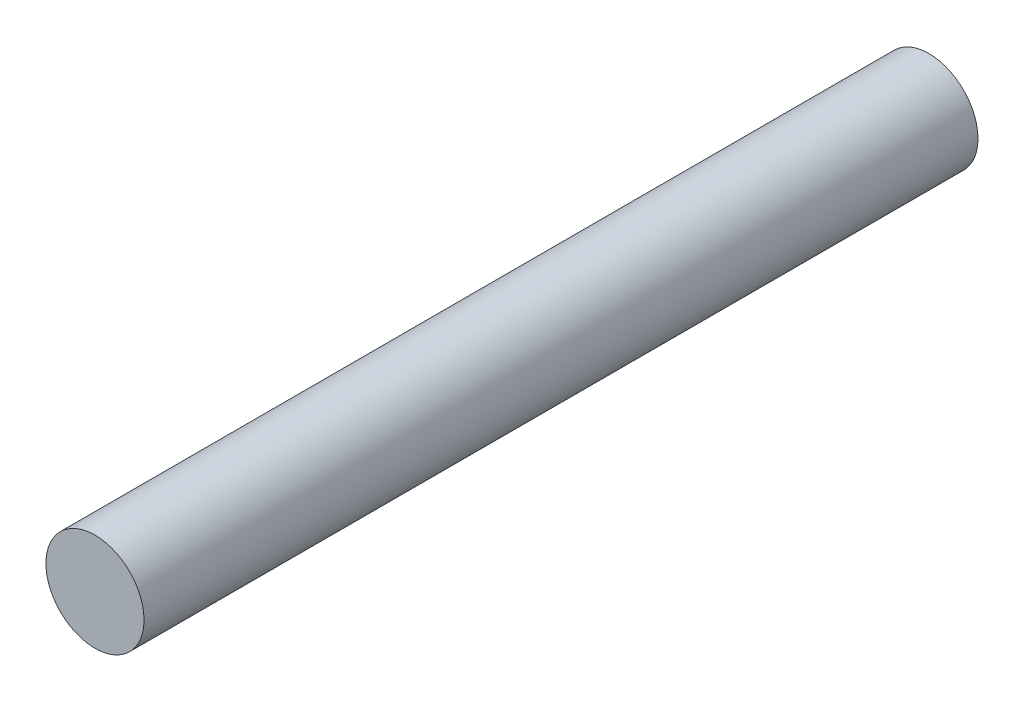
SolidWorks part; units mm, degrees
ref_plane "Plan de face" through (0, 0, 0) normal (0, 0, 1) x (1, 0, 0)
ref_plane "Plan de dessus" through (0, 0, 0) normal (0, 1, 0) x (1, 0, 0)
ref_plane "Plan de droite" through (0, 0, 0) normal (1, 0, 0) x (0, 0, -1)
sketch "Esquisse1" plane through (0, 0, 0) normal (0, 0, 1) x (1, 0, 0)
  circle A0 centre (0, 0) radius 4
  dimension "D1" = 8
extrude "Extrusion1" add sketch "Esquisse1" against normal blind 68
